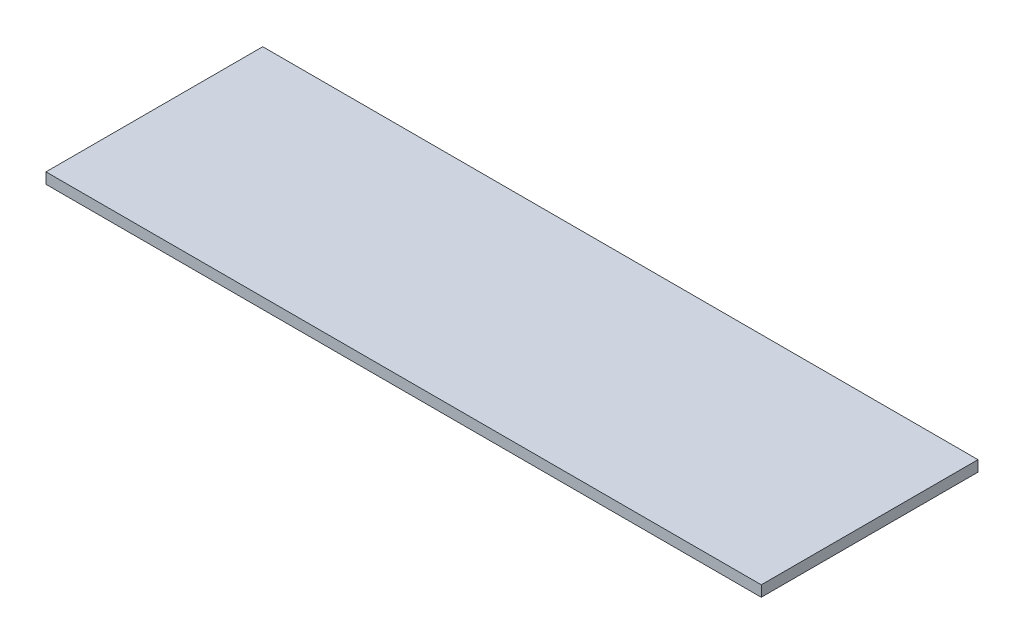
SolidWorks part; units mm, degrees
ref_plane "Alzado" through (0, 0, 0) normal (0, 0, 1) x (1, 0, 0)
ref_plane "Planta" through (0, 0, 0) normal (0, 1, 0) x (1, 0, 0)
ref_plane "Vista lateral" through (0, 0, 0) normal (1, 0, 0) x (0, 0, -1)
sketch "Croquis1" plane through (0, 0, 0) normal (0, 1, 0) x (1, 0, 0)
  line L1 (-594, 180) -> (594, 180)
  line L2 (-594, 180) -> (-594, -180)
  line L3 (-594, -180) -> (594, -180)
  line L4 (594, 180) -> (594, -180)
  line L5 (-594, 180) -> (594, -180) construction
  line L6 (-594, -180) -> (594, 180) construction
  point P0 (0, 0)
  dimension "D1" = 1188
  dimension "D2" = 360
extrude "Saliente-Extruir1" add sketch "Croquis1" along normal blind 18
